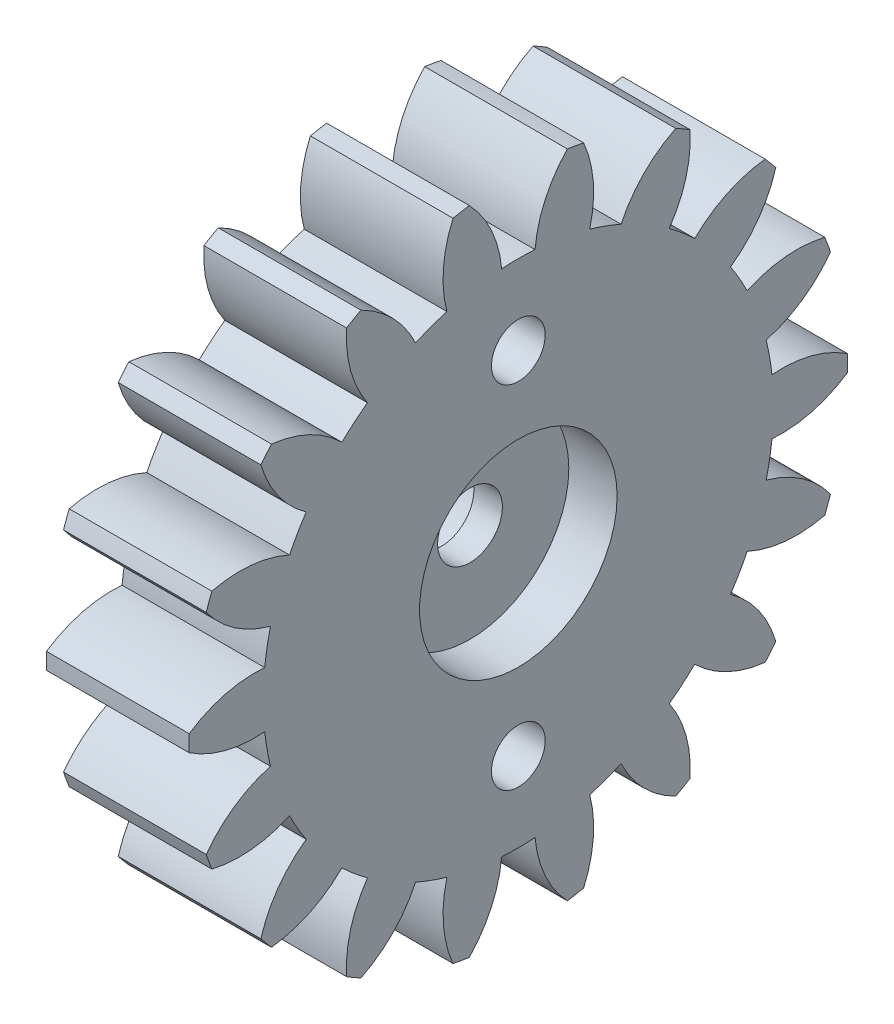
SolidWorks part; units mm, degrees
ref_plane "Plane1" through (0, 0, 0) normal (0, 0, 1) x (1, 0, 0)
ref_plane "Plane2" through (0, 0, 0) normal (0, 1, 0) x (1, 0, 0)
ref_plane "Plane3" through (0, 0, 0) normal (1, 0, 0) x (0, 0, -1)
sketch "HoldingSke" plane through (0, 0, 0) normal (0, 1, 0) x (1, 0, 0)
  line L0 (0, 0) -> (0.634, -0.206)
  line L1 (-15, 0) -> (100, 0) construction
  line L2 (0, 0) -> (-2.1039, 2.3779)
  line L3 (0, 0) -> (-11.863, 4.5341)
  line L4 (0, 0) -> (8.2133, 2.6687)
  line L5 (0, 0) -> (-46.8476, -17.4728)
  line L6 (0, 0) -> (-5.3883, -3.6355)
  line L7 (-2.1039, 2.3779) -> (8.6586, 51.2059)
  line L8 (-76.2, 54.61) -> (-76.1, 54.61)
  line L9 (-71.009, 38.7566) -> (-53.1078, 45.2721)
  line L10 (-76.2, 71.12) -> (104.1128, 71.12)
  line L11 (0, 0) -> (-6.5, 0)
  line L12 (-76.2, 101.6) -> (-76.147, 101.6)
  line L13 (24.9733, 27.94) -> (52.9518, 28.4284)
  line L14 (24.9733, 27.94) -> (24.9743, 27.94)
  line L15 (24.9733, 27.94) -> (100.4006, 29.5858)
  line L16 (-63.627, -1.5) -> (-12.827, -1.5)
  circle A0 centre (0, 0) radius 0.4
  circle A1 centre (0, 0) radius 11.624
  circle A2 centre (0, 0) radius 37.5
  circle A3 centre (0, 0) radius 0.4
  dimension "MHD" = 23.248
  dimension "Hub_dia" = 75
  dimension "Bore" = 0.8
  dimension "MBD" = 0.8
  dimension "Num_teeth" = 18
  dimension "Pitch" = 0.6667
  dimension "Overall_len" = 50
  dimension "Show_teeth" = 18
  dimension "Thickness" = 6.5
  dimension "OAL" = 50.0001
  dimension "T_dim" = 0.1
  dimension "Ap" = 20
  dimension "H" = 19.05
  dimension "Pitch_radius" = 180.3128
  dimension "Width" = 6.5
  dimension "Backlash" = 0.053
  dimension "Addendum_fac" = 1
  dimension "Dedendum_fac" = 1.25
  dimension "Clearance_fac" = 0.25
  dimension "Dedendum_add" = 0.001
  dimension "Module" = 1.5
sketch "BasProSke" plane through (0, 0, 0) normal (0, 1, 0) x (1, 0, 0)
  line L0 (-10, 0) -> (60, 0) construction
  line L1 (0, 0) -> (0, 15)
  line L2 (0, 0) -> (6.5, 0)
  line L3 (6.5, 0) -> (6.5, 15)
  line L4 (6.5, 15) -> (0, 15)
  dimension "Thickness" = 6.5
  dimension "Diameter" = 30
revolve "Base-Revolve" add sketch "BasProSke" angle 360 about L0
sketch "TooCutSke" plane through (0, 0, 0) normal (1, 0, 0) x (0, 0, -1)
  line L1 (0, 0) -> (0, 107) construction
  line L2 (0, 0) -> (-1.2693, 13.4402) construction
  line L3 (0, 0) -> (-4.6734, 26.504) construction
  line L4 (-1.2693, 13.4402) -> (-2.3367, 13.252) construction
  arc A0 (0.76, 11.5991) -> (-0.76, 11.5991) centre (0, 0) ccw
  arc A1 (2.2542, 14.8553) -> (-2.2542, 14.8553) centre (0, 0) ccw
  circle A2 centre (0, 0) radius 13.5 construction
  circle A3 centre (0, 0) radius 12.6859 construction
  arc A4 (-0.76, 11.5991) -> (-2.2542, 14.8553) centre (-6.1371, 11.1026) ccw
  arc A5 (2.2542, 14.8553) -> (0.76, 11.5991) centre (6.1371, 11.1026) ccw
  dimension "Root_dia" = 23.248
  dimension "Overcut_dia" = 30.0508
  dimension "Pitch_dia" = 27
  dimension "Base_dia" = 25.3717
  dimension "Flank_rad" = 5.4
  dimension "Half_ang" = 10
  dimension "Half_CT" = 1.0839
extrude "ToothCut" cut sketch "TooCutSke" along normal through all
fillet "Breaks" [suppressed] radius 0.03
fillet "RootFillets" [suppressed] radius 0.376
pattern_circular "TeethCuts" count 18 every 20 about axis through (-10, 0, 0) along (1, 0, 0) of "ToothCut", "RootFillets", "Breaks"
sketch "HubNeaOneSke" plane through (0, 0, 0) normal (-1, 0, 0) x (0, 0, 1)
  circle A0 centre (0, 0) radius 11.624
  dimension "Diameter" = 23.248
extrude "HubNearOne" [suppressed] add sketch "HubNeaOneSke" along normal blind 43.5001
sketch "HubNeaBotSke" plane through (0, 0, 0) normal (-1, 0, 0) x (0, 0, 1)
  circle A0 centre (0, 0) radius 11.624
  dimension "Diameter" = 23.248
extrude "HubNearBoth" [suppressed] add sketch "HubNeaBotSke" along normal blind 21.75
ref_plane "FarPln" through (6.5, 0, 0) normal (1, 0, 0) x (0, 0, -1)
sketch "HubFarSke" plane through (6.5, 0, 0) normal (1, 0, 0) x (0, 0, -1)
  circle A0 centre (0, 0) radius 11.624
  dimension "Diameter" = 23.248
extrude "HubFar" [suppressed] add sketch "HubFarSke" along normal blind 21.75
sketch "BorSke" plane through (0, 0, 0) normal (1, 0, 0) x (0, 0, -1)
  circle A0 centre (0, 0) radius 0.4
  dimension "Diameter" = 0.8
extrude "Bore" cut sketch "BorSke" along normal mid plane 100.0001
sketch "KeySke" plane through (0, 0, 0) normal (1, 0, 0) x (0, 0, -1)
  line L0 (-0.05, 0) -> (-0.05, 0.5)
  line L1 (-0.05, 0.5) -> (0.05, 0.5)
  line L2 (0.05, 0.5) -> (0.05, 0)
  line L3 (0, 0) -> (0, 34) construction
  line L4 (-0.05, 0) -> (0.05, 0)
  dimension "Offset" = 0.5
  dimension "Width" = 0.1
extrude "Keyway" [suppressed] cut sketch "KeySke" along normal mid plane 100.0001
pattern_circular "Keyway2" [suppressed] count 2 every 90 about axis through (-10, 0, 0) along (1, 0, 0)
sketch "草图1" plane through (6.5, 0, 0) normal (1, 0, 0) x (0, 0, -1)
  circle A0 centre (0, 0) radius 4.5
  dimension "D1" = 9
extrude "切除-拉伸1" cut sketch "草图1" against normal blind 2.2
sketch "草图2" plane through (4.3, 0, 0) normal (1, 0, 0) x (0, 0, -1)
  circle A0 centre (0, 0) radius 1.475
  dimension "D1" = 2.95
extrude "切除-拉伸2" cut sketch "草图2" against normal through all
sketch "草图3" plane through (6.5, 0, 0) normal (1, 0, 0) x (0, 0, -1)
  line L0 (0, 0) -> (0, -8)
  line L1 (0, 0) -> (0, 8)
  circle A0 centre (0, -8) radius 1.225
  circle A1 centre (0, 8) radius 1.225
  dimension "D1" = 2.45
  dimension "D2" = 2.45
extrude "切除-拉伸3" cut sketch "草图3" against normal through all contours A1 | A0
sketch "草图4" plane through (0, 0, 0) normal (-1, 0, 0) x (0, 0, 1)
  circle A0 centre (0, -8) radius 2.15
  circle A1 centre (0, 8) radius 2.15
  dimension "D1" = 4.3
  dimension "D2" = 4.3
extrude "切除-拉伸5" cut sketch "草图4" against normal blind 2.2
sketch "草图5" plane through (0, 0, 0) normal (-1, 0, 0) x (0, 0, 1)
  circle A0 centre (0, 0) radius 2.5
extrude "切除-拉伸6" cut sketch "草图5" against normal blind 3
sketch "草图6" plane through (0, 0, 0) normal (-1, 0, 0) x (0, 0, 1)
  circle A0 centre (0, 0) radius 15
equation "' \"Module@HoldingSke\" = 6.35"
equation "' \"Num_teeth@HoldingSke\" = 12"
equation "' \"Ap@HoldingSke\" =  20"
equation "' \"Ap@HoldingSke\" = 20"
equation "' \"Width@HoldingSke\" = 0.5 * 25.4"
equation "' \"Hub_dia@HoldingSke\"= 1 * 25.4"
equation "' \"Hub_dia@HoldingSke\" = 1 * 25.4"
equation "' \"Overall_len@HoldingSke\" = 1.0 * 25.4"
equation "' \"Bore@HoldingSke\" = 0.75 * 25.4"
equation "' \"T_dim@HoldingSke\" = 0.1 * 25.4"
equation "' \"Width@KeySke\" = 0.25 * 25.4"
equation "' \"Show_teeth@HoldingSke\" = 13"
equation "' \"Backlash@HoldingSke\" = 0.009 * 25.4"
equation "' \"Addendum_fac@HoldingSke\" = 1.0"
equation "' \"Dedendum_fac@HoldingSke\" = 1.25"
equation "' \"Dedendum_add@HoldingSke\" = 0.00005 * 25.4"
equation "' \"Clearance_fac@HoldingSke\" = 0.25"
equation "\"Pitch@HoldingSke\" = 1 / \"Module@HoldingSke\""
equation "\"Overcut_dia@TooCutSke\" = (\"Num_teeth@HoldingSke\" + 2 * \"Addendum_fac@HoldingSke\") / \"Pitch@HoldingSke\" + 0.002 * 25.4"
equation "\"Pitch_dia@TooCutSke\" = \"Num_teeth@HoldingSke\" / \"Pitch@HoldingSke\""
equation "\"Base_dia@TooCutSke\" = \"Num_teeth@HoldingSke\" / \"Pitch@HoldingSke\" * cos((\"Ap@HoldingSke\"  * 3.14159265 / 180))"
equation "\"Root_dia@TooCutSke\" = (\"Num_teeth@HoldingSke\" + 2) / \"Pitch@HoldingSke\" - 2 * (\"Addendum_fac@HoldingSke\" + \"Dedendum_fac@HoldingSke\") / \"Pitch@HoldingSke\" - \"Dedendum_add@HoldingSke\" * 2"
equation "\"Half_ang@TooCutSke\" = 180 / \"Num_teeth@HoldingSke\""
equation "\"Half_CT@TooCutSke\" = \"Num_teeth@HoldingSke\" / \"Pitch@HoldingSke\" * sin((3.14159265 / 2 / \"Num_teeth@HoldingSke\")) / 2 - 7 * \"Backlash@HoldingSke\" / 4"
equation "\"Flank_rad@TooCutSke\" = \"Num_teeth@HoldingSke\" / \"Pitch@HoldingSke\" / 5"
equation "\"Radius@RootFillets\" = \"Clearance_fac@HoldingSke\" / \"Pitch@HoldingSke\" + \"Dedendum_add@HoldingSke\""
equation "\"Break_rad@Breaks\" = 0.02 / \"Pitch@HoldingSke\""
equation "\"Thickness@HoldingSke\" = \"Width@HoldingSke\""
equation "\"OAL@HoldingSke\" = \"Thickness@HoldingSke\""
equation "\"MHD@HoldingSke\" = (\"Num_teeth@HoldingSke\" + 2) / \"Pitch@HoldingSke\" - 2 * (\"Addendum_fac@HoldingSke\" + \"Dedendum_fac@HoldingSke\")  / \"Pitch@HoldingSke\" - \"Dedendum_add@HoldingSke\" * 2"
equation "\"MBD@HoldingSke\" = (\"Num_teeth@HoldingSke\" + 2) / \"Pitch@HoldingSke\" - 2 * (\"Addendum_fac@HoldingSke\" + \"Dedendum_fac@HoldingSke\")  / \"Pitch@HoldingSke\" - \"Dedendum_add@HoldingSke\" * 2 - 0.002 * 25.4"
equation "\"MHD@HoldingSke\" = ((sgn( \"MHD@HoldingSke\" - \"Hub_dia@HoldingSke\" )-1)*( \"MHD@HoldingSke\" - \"Hub_dia@HoldingSke\" ))/-2+ \"Hub_dia@HoldingSke\""
equation "\"MBD@HoldingSke\" = ((sgn( \"MBD@HoldingSke\" - \"Bore@HoldingSke\" )-1)*( \"MBD@HoldingSke\" - \"Bore@HoldingSke\" ))/-2+ \"Bore@HoldingSke\""
equation "\"OAL@HoldingSke\" = ((sgn( \"OAL@HoldingSke\" - \"Overall_len@HoldingSke\" )+1)*( \"OAL@HoldingSke\" - \"Overall_len@HoldingSke\" ))/2 + \"Overall_len@HoldingSke\" + 0.000002 * 25.4"
equation "\"Num_teeth@TeethCuts\" = int( \"Show_teeth@HoldingSke\" ) + 1"
equation "\"Num_teeth@TeethCuts\" = ((sgn( \"Num_teeth@TeethCuts\" - \"Num_teeth@HoldingSke\" )-1)*( \"Num_teeth@TeethCuts\" - \"Num_teeth@HoldingSke\" ))/-2+ \"Num_teeth@HoldingSke\""
equation "\"Num_teeth@TeethCuts\" = ((sgn( \"Num_teeth@TeethCuts\" - 2.0)+1)*( \"Num_teeth@TeethCuts\" - 2.0))/2 +2.0"
equation "\"Angle@TeethCuts\" = 360.0 / \"Num_teeth@HoldingSke\""
equation "\"Diameter@BasProSke\" = (\"Num_teeth@HoldingSke\" + 2 * \"Addendum_fac@HoldingSke\") / \"Pitch@HoldingSke\""
equation "\"Thickness@BasProSke\"  = \"Thickness@HoldingSke\""
equation "' \"Fillet_rad@BasProSke\" =  \"Thickness@HoldingSke\" * 0.05"
equation "' \"Fillet_rad@BasProSke\" = \"Thickness@HoldingSke\" * 0.05"
equation "\"MHD@HoldingSke\" = ((sgn( \"MHD@HoldingSke\" - \"Root_dia@TooCutSke\" )-1)*( \"MHD@HoldingSke\" - \"Root_dia@TooCutSke\" ))/-2+ \"Root_dia@TooCutSke\""
equation "\"Diameter@HubNeaOneSke\" = \"MHD@HoldingSke\""
equation "\"Length@HubNearOne\" = \"OAL@HoldingSke\" - \"Thickness@BasProSke\""
equation "\"Diameter@HubNeaBotSke\" = \"MHD@HoldingSke\""
equation "\"Length@HubNearBoth\" = ( \"OAL@HoldingSke\" - \"Thickness@BasProSke\" ) / 2.0"
equation "\"Thickness@FarPln\" = \"Thickness@BasProSke\""
equation "\"Diameter@HubFarSke\" = \"MHD@HoldingSke\""
equation "\"Length@HubFar\" = ( \"OAL@HoldingSke\" - \"Thickness@BasProSke\" ) / 2.0"
equation "\"Diameter@BorSke\" = \"MBD@HoldingSke\""
equation "\"D1@Bore\" = \"OAL@HoldingSke\" * 2.0"
equation "\"D1@Keyway\" = \"OAL@HoldingSke\" * 2.0"
equation "\"Offset@KeySke\" = \"T_dim@HoldingSke\" + \"MBD@HoldingSke\" / 2.0"
